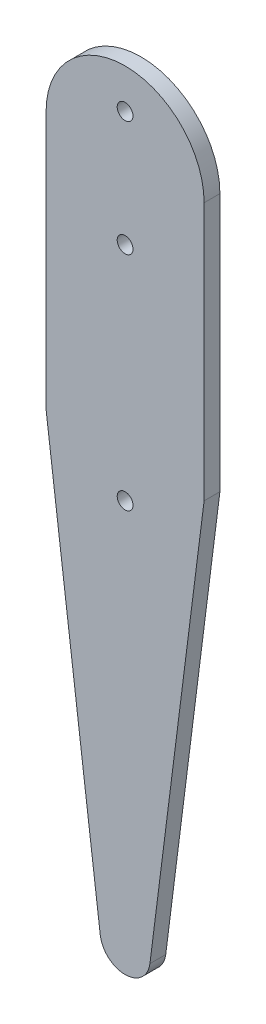
SolidWorks part; units mm, degrees
ref_plane "Front Plane" through (0, 0, 0) normal (0, 0, 1) x (1, 0, 0)
ref_plane "Top Plane" through (0, 0, 0) normal (0, 1, 0) x (1, 0, 0)
ref_plane "Right Plane" through (0, 0, 0) normal (1, 0, 0) x (0, 0, -1)
sketch "Sketch1" plane through (0, 0, 0) normal (0, 0, 1) x (1, 0, 0)
  line L0 (-5, -1011.6385) -> (-5, 48988.3615) construction
  line L5 (10, -959.5) -> (10, 49040.5) construction
  line L6 (5.25, -1016.8654) -> (5.25, -85.1896) construction
  line L7 (14.75, -1019.8958) -> (14.75, 48980.1042) construction
  line L8 (25, -978.4803) -> (25, 49021.5197) construction
  line L9 (-979.0853, 44.75) -> (49020.9147, 44.75) construction
  line L10 (-999.9631, -4.25) -> (49000.0369, -4.25) construction
  line L11 (-5, 44.75) -> (-5, -4.25)
  line L12 (25, 44.75) -> (25, -4.25)
  line L13 (-1010.4081, 30.36) -> (48989.5919, 30.36) construction
  line L14 (-990, -89.64) -> (49010, -89.64) construction
  line L15 (-5, -4.25) -> (5.2876, -85.4868)
  line L16 (25, -4.25) -> (14.7124, -85.4868)
  line L17 (5.25, -6.5) -> (5.25, 48983.1346) construction
  circle A0 centre (10, 30.36) radius 1.5
  arc A4 (25, 44.75) -> (-5, 44.75) centre (10, 44.75) ccw
  arc A5 (5.2876, -85.4868) -> (14.7124, -85.4868) centre (10, -84.89) ccw
  circle A6 centre (10, 52.25) radius 1.5
  circle A7 centre (10, -11.75) radius 1.5
  dimension "D15" = 4.75
  dimension "D16" = 3
  dimension "D17" = 3
  dimension "D18" = 7.5
  dimension "D4" = 3
  dimension "D2" = 4.75
  dimension "D3" = 4.75
  dimension "D13" = 49
  dimension "D14" = 120
  dimension "D19" = 7.5
extrude "Boss-Extrude1" add sketch "Sketch1" along normal blind 3
